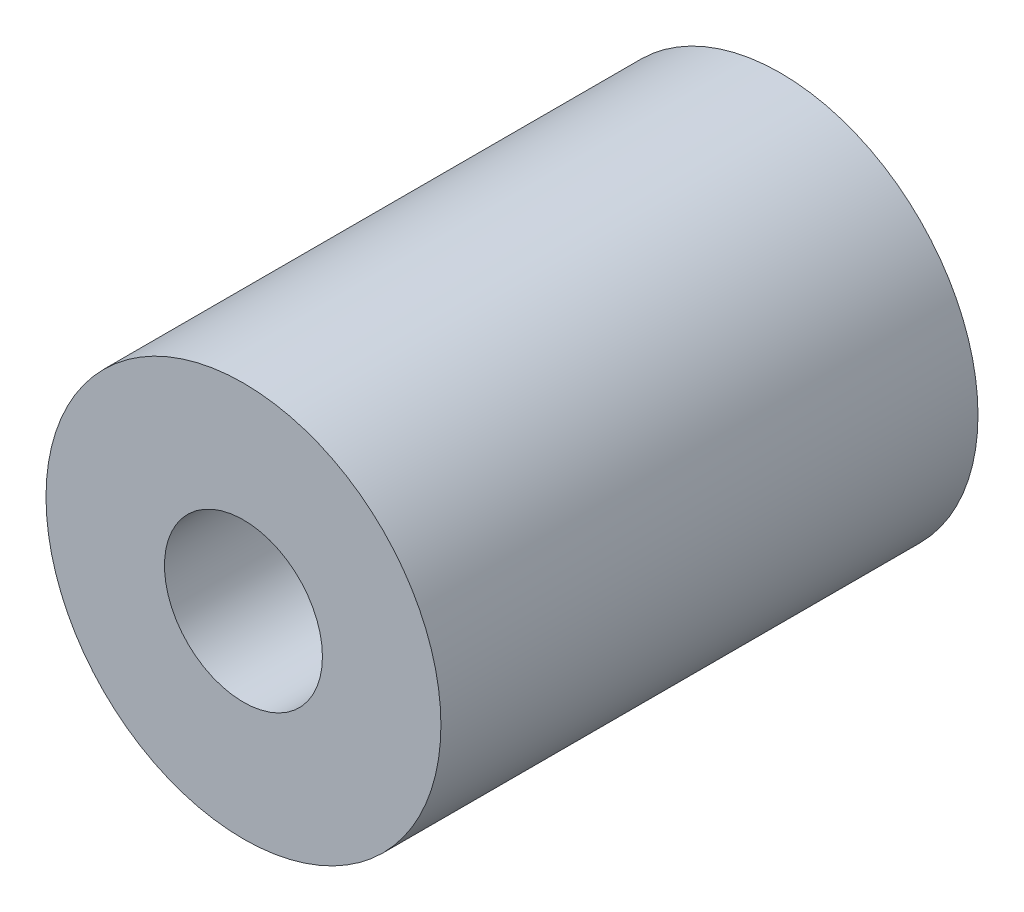
SolidWorks part; units mm, degrees
ref_plane "前视基准面" through (0, 0, 0) normal (0, 0, 1) x (1, 0, 0)
ref_plane "上视基准面" through (0, 0, 0) normal (0, 1, 0) x (1, 0, 0)
ref_plane "右视基准面" through (0, 0, 0) normal (1, 0, 0) x (0, 0, -1)
sketch "草图1" plane through (0, 0, 0) normal (0, 0, 1) x (1, 0, 0)
  circle A0 centre (0, 0) radius 6
  circle A1 centre (0, 0) radius 15
extrude "凸台-拉伸1" add sketch "草图1" along normal blind 40.8
